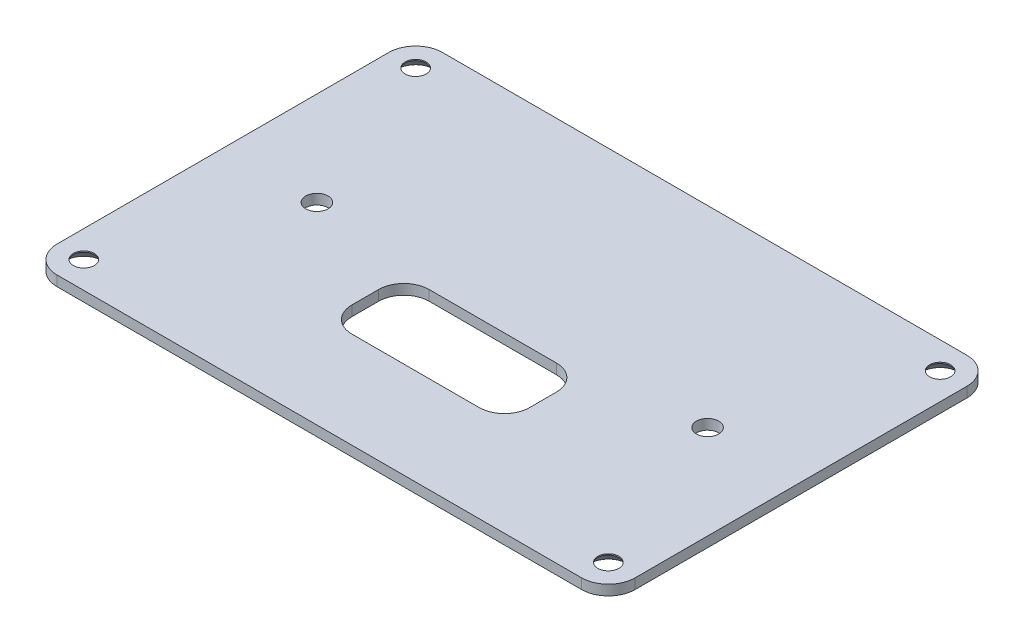
SolidWorks part; units mm, degrees
material "Plain Carbon Steel"
ref_plane "Front" through (0, 0, 0) normal (0, 0, 1) x (1, 0, 0)
ref_plane "Top" through (0, 0, 0) normal (0, 1, 0) x (1, 0, 0)
ref_plane "Right" through (0, 0, 0) normal (1, 0, 0) x (0, 0, -1)
sketch "Sketch1" plane through (0, 0, 0) normal (0, 1, 0) x (1, 0, 0)
  line L0 (-45, 0) -> (45, 0) construction
  line L1 (-45, 30) -> (45, 30) construction
  line L2 (-45, 30) -> (-45, -30) construction
  line L3 (-45, -30) -> (45, -30) construction
  line L4 (45, 30) -> (45, -30) construction
  line L5 (0, -30) -> (0, 30) construction
  line L6 (41.825, 26.825) -> (41.825, -26.825) construction
  line L7 (-41.825, -26.825) -> (41.825, -26.825) construction
  line L8 (-41.825, 26.825) -> (-41.825, -26.825) construction
  line L9 (-41.825, 26.825) -> (41.825, 26.825) construction
  line L10 (40.825, 25.825) -> (40.825, -25.825) construction
  line L11 (-40.825, -25.825) -> (40.825, -25.825) construction
  line L12 (-40.825, 25.825) -> (-40.825, -25.825) construction
  line L13 (-40.825, 25.825) -> (40.825, 25.825) construction
  line L14 (40.825, 21.65) -> (45, 21.65) construction
  line L15 (40.825, -21.65) -> (45, -21.65) construction
  line L16 (36.65, -25.825) -> (36.65, -30) construction
  line L17 (-36.65, -25.825) -> (-36.65, -30) construction
  line L18 (-40.825, -21.65) -> (-45, -21.65) construction
  line L19 (-36.65, 25.825) -> (-36.65, 30) construction
  line L20 (-40.825, 21.65) -> (-45, 21.65) construction
  line L21 (36.65, 25.825) -> (36.65, 30) construction
  line L22 (40.825, -25.825) -> (41.825, -25.825) construction
  circle A0 centre (-40.825, -25.825) radius 1 construction
  circle A1 centre (40.825, -25.825) radius 1 construction
  circle A2 centre (40.825, 25.825) radius 1 construction
  circle A3 centre (-40.825, 25.825) radius 1 construction
  circle A4 centre (40.825, -25.825) radius 4.175 construction
  circle A5 centre (40.825, 25.825) radius 4.175 construction
  circle A6 centre (-40.825, 25.825) radius 4.175 construction
  circle A7 centre (-40.825, -25.825) radius 4.175 construction
  dimension "D1" = 90
  dimension "D2" = 60
  dimension "D4" = 1
  dimension "D3" = 3.175
sketch "Sketch2" plane through (0, 0, 0) normal (0, 1, 0) x (1, 0, 0)
  line L0 (-45, 30) -> (-45, -30) construction
  line L1 (-45, -30) -> (45, -30) construction
  line L2 (45, 30) -> (45, -30) construction
  line L3 (-45, 30) -> (45, 30) construction
  line L16 (-45, 25.825) -> (-45, -25.825)
  line L17 (-40.825, -30) -> (40.825, -30)
  line L18 (45, 25.825) -> (45, -25.825)
  line L19 (-40.825, 30) -> (40.825, 30)
  circle A0 centre (40.825, 25.825) radius 4.175 construction
  circle A1 centre (40.825, 25.825) radius 1 construction
  circle A2 centre (-40.825, 25.825) radius 4.175 construction
  circle A3 centre (-40.825, 25.825) radius 1 construction
  arc A6 (45, 25.825) -> (40.825, 30) centre (40.825, 25.825) ccw
  circle A7 centre (40.825, 25.825) radius 1
  arc A8 (-40.825, 30) -> (-45, 25.825) centre (-40.825, 25.825) ccw
  circle A9 centre (-40.825, 25.825) radius 1
  circle A12 centre (-40.825, -25.825) radius 1 construction
  circle A13 centre (40.825, -25.825) radius 1 construction
  circle A14 centre (-40.825, -25.825) radius 1
  circle A15 centre (40.825, -25.825) radius 1
  arc A17 (-45, -25.825) -> (-40.825, -30) centre (-40.825, -25.825) ccw
  arc A18 (40.825, -30) -> (45, -25.825) centre (40.825, -25.825) ccw
extrude "Boss-Extrude3" add sketch "Sketch2" along normal blind 1.5875
sketch "Sketch4" plane through (0, 0, 0) normal (0, -1, 0) x (1, 0, 0)
  line L10 (-13.335, 6.9246) -> (-13.335, 11.0902) construction
  line L11 (-9.906, 14.5192) -> (9.906, 14.5192) construction
  line L12 (13.335, 6.9246) -> (13.335, 11.0902) construction
  line L13 (-9.906, 3.4956) -> (9.906, 3.4956) construction
  line L14 (-13.335, 6.9246) -> (-13.335, 11.0902) construction
  line L15 (-9.906, 14.5192) -> (9.906, 14.5192) construction
  line L16 (13.335, 6.9246) -> (13.335, 11.0902) construction
  line L17 (-9.906, 3.4956) -> (9.906, 3.4956) construction
  line L18 (-13.835, 6.9246) -> (-13.835, 11.0902)
  line L19 (-9.906, 15.0192) -> (9.906, 15.0192)
  line L20 (13.835, 6.9246) -> (13.835, 11.0902)
  line L21 (-9.906, 2.9956) -> (9.906, 2.9956)
  arc A4 (-9.906, 14.5192) -> (-13.335, 11.0902) centre (-9.906, 11.0902) ccw construction
  arc A5 (13.335, 11.0902) -> (9.906, 14.5192) centre (9.906, 11.0902) ccw construction
  arc A6 (9.906, 3.4956) -> (13.335, 6.9246) centre (9.906, 6.9246) ccw construction
  arc A7 (-13.335, 6.9246) -> (-9.906, 3.4956) centre (-9.906, 6.9246) ccw construction
  arc A8 (-9.906, 14.5192) -> (-13.335, 11.0902) centre (-9.906, 11.0902) ccw construction
  arc A9 (13.335, 11.0902) -> (9.906, 14.5192) centre (9.906, 11.0902) ccw construction
  arc A10 (9.906, 3.4956) -> (13.335, 6.9246) centre (9.906, 6.9246) ccw construction
  arc A11 (-13.335, 6.9246) -> (-9.906, 3.4956) centre (-9.906, 6.9246) ccw construction
  arc A12 (-9.906, 15.0192) -> (-13.835, 11.0902) centre (-9.906, 11.0902) ccw
  arc A13 (13.835, 11.0902) -> (9.906, 15.0192) centre (9.906, 11.0902) ccw
  arc A14 (9.906, 2.9956) -> (13.835, 6.9246) centre (9.906, 6.9246) ccw
  arc A15 (-13.835, 6.9246) -> (-9.906, 2.9956) centre (-9.906, 6.9246) ccw
  dimension "D1" = 0.5
extrude "DB15 Plug Cutaway" cut sketch "Sketch4" against normal through all
hole_wizard "CSK for #4 Flat Head Machine Screw1" positions "Sketch10" profile "Sketch9" countersink size "#4" standard "ANSI Inch" end condition through all
sketch "Sketch10" plane through (0, 0, 0) normal (0, -1, 0) x (-1, 0, 0)
  point P0 (40.825, -25.825)
  point P5 (40.825, 25.825)
  point P9 (-40.825, -25.825)
  point P13 (-40.825, 25.825)
sketch "Sketch9" plane through (-40.825, 0, 25.825) normal (1, 0, 0) x (0, 0, -1)
  line L0 (0, 0) -> (0, 1.5875)
  line L1 (0, 1.5875) -> (1.6319, 1.5875)
  line L2 (1.6319, 1.5875) -> (1.6319, 1.4098)
  line L3 (1.6319, 1.4098) -> (2.8575, 0)
  line L5 (2.8575, 0) -> (0, 0)
  line L6 (-1.632, 1.4098) -> (-2.8575, 0) construction
  line L11 (0, -6.35) -> (0, 107.95) construction
  dimension "Thru Hole Dia." = 3.2639
  dimension "Thru Hole Depth" = 1.5875
  dimension "Near C'Sink Dia." = 5.715
  dimension "Near C'Sink Angle" = 82
sketch "Sketch11" plane through (0, 0, 0) normal (0, -1, 0) x (1, 0, 0)
  line L0 (40.825, -25.825) -> (-40.825, -25.825) construction
  line L1 (-40.825, -25.825) -> (-40.825, 25.825) construction
  line L2 (-40.825, 25.825) -> (40.825, 25.684) construction
  line L3 (40.825, 25.684) -> (40.825, -25.825) construction
  line L4 (40.825, -0.0705) -> (-40.825, 0) construction
  line L5 (19.939, 9.0074) -> (40.825, 9.0074) construction
  line L6 (19.939, 13.935) -> (19.939, 4.0798) construction
  line L8 (-19.939, 9.0074) -> (-40.825, 9.0074) construction
  line L9 (-19.939, 13.935) -> (-19.939, 4.0798) construction
  line L10 (-30.382, 9.0074) -> (-30.382, -0.009) construction
  line L11 (30.382, 9.0074) -> (30.382, -0.0615) construction
  circle A0 centre (-30.382, -0.009) radius 1.7399
  circle A1 centre (30.382, -0.0615) radius 1.7399
  dimension "D1" = 3.4798
  dimension "D2" = 3.4798
extrude "Cut-Extrude1" cut sketch "Sketch11" against normal through all
